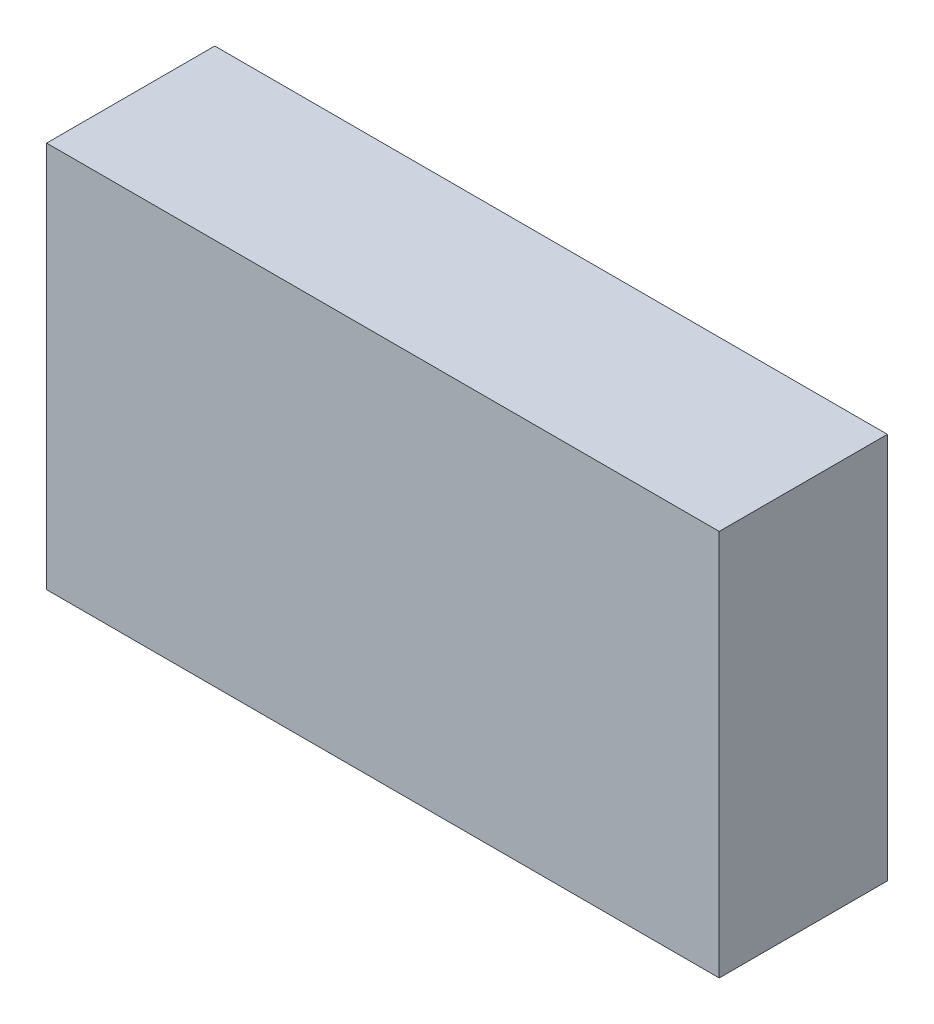
SolidWorks part; units mm, degrees
ref_plane "Front Plane" through (0, 0, 0) normal (0, 0, 1) x (1, 0, 0)
ref_plane "Top Plane" through (0, 0, 0) normal (0, 1, 0) x (1, 0, 0)
ref_plane "Right Plane" through (0, 0, 0) normal (1, 0, 0) x (0, 0, -1)
sketch "RectangleSketch" plane through (0, 0, 0) normal (0, 0, 1) x (1, 0, 0)
  line L1 (0, 0) -> (40, 0)
  line L2 (0, 0) -> (0, 23)
  line L3 (0, 23) -> (40, 23)
  line L4 (40, 0) -> (40, 23)
  dimension "width_mm" = 40
  dimension "height_mm" = 23
extrude "BlindBoss" add sketch "RectangleSketch" along normal blind 10 separate body
